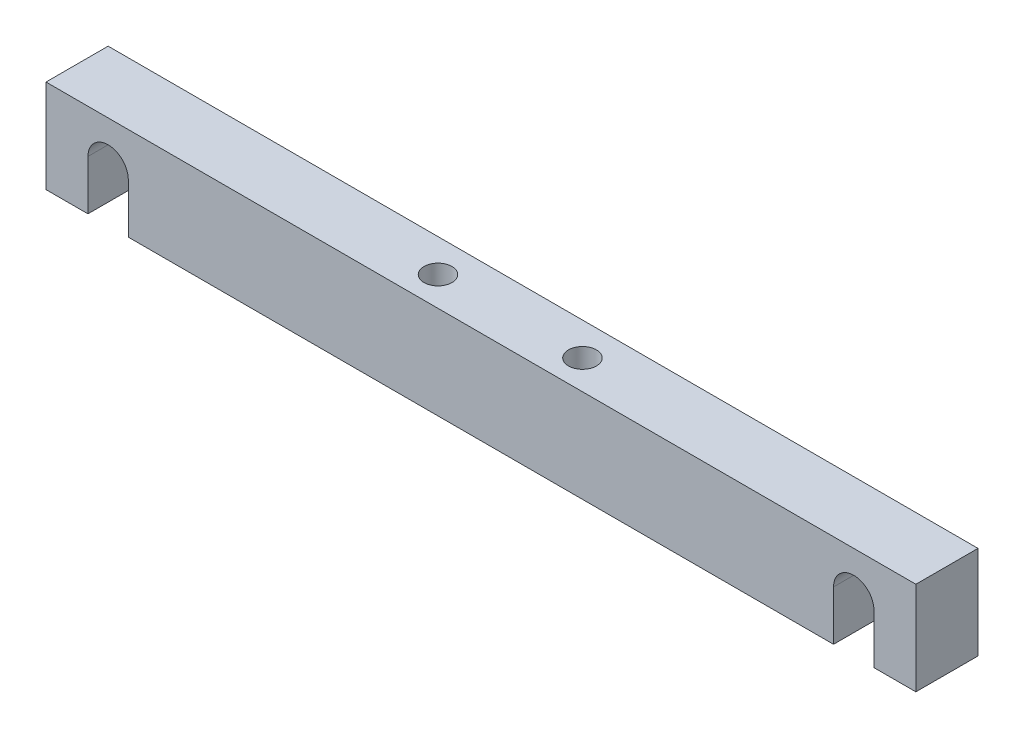
SolidWorks part; units mm, degrees
material "3.3547 (EN-AW 5083)"
ref_plane "Ebene vorne" through (0, 0, 0) normal (0, 0, 1) x (1, 0, 0)
ref_plane "Ebene oben" through (0, 0, 0) normal (0, 1, 0) x (1, 0, 0)
ref_plane "Ebene rechts" through (0, 0, 0) normal (1, 0, 0) x (0, 0, -1)
sketch "Skizze1" plane through (0, 0, 0) normal (0, 1, 0) x (1, 0, 0)
  line L1 (23.8745, 5.2866) -> (163.8745, 5.2866)
  line L2 (23.8745, 5.2866) -> (23.8745, -4.7134)
  line L3 (23.8745, -4.7134) -> (163.8745, -4.7134)
  line L4 (163.8745, 5.2866) -> (163.8745, -4.7134)
  dimension "D1" = 10
  dimension "D2" = 140
extrude "Aufsatz-Linear austragen1" add sketch "Skizze1" along normal blind 15
sketch "Skizze2" plane through (0, 0, -5.2866) normal (0, 0, -1) x (-1, 0, 0)
  line L0 (-163.8745, 15) -> (-23.8745, 15) construction
  line L1 (-37.1245, 8) -> (-37.1245, 0)
  line L2 (-163.8745, 0) -> (-23.8745, 0) construction
  line L3 (-37.1245, 0) -> (-30.6245, 0)
  line L4 (-30.6245, 0) -> (-30.6245, 8)
  line L5 (-23.8745, 15) -> (-23.8745, 0) construction
  line L6 (-157.1245, 8) -> (-157.1245, -0.1204)
  line L7 (-157.1245, -0.1204) -> (-150.6245, -0.1204)
  line L8 (-150.6245, -0.1204) -> (-150.6245, 8)
  arc A0 (-30.6245, 8) -> (-37.1245, 8) centre (-33.8745, 8) ccw
  arc A1 (-150.6245, 8) -> (-157.1245, 8) centre (-153.8745, 8) ccw
  dimension "D1" = 7
  dimension "D2" = 10
  dimension "D3" = 3.25
  dimension "D4" = 120
  dimension "D5" = 7
extrude "Schnitt-Linear austragen1" cut sketch "Skizze2" against normal blind 15
sketch "Skizze3" plane through (0, 0, 0) normal (0, -1, 0) x (1, 0, 0)
  line L0 (23.8745, -5.2866) -> (23.8745, 4.7134) construction
  circle A0 centre (82.2495, 0) radius 1.604
  circle A1 centre (105.4995, 0) radius 1.3762
  dimension "D2" = 58.375
  dimension "D1" = 81.625
hole_wizard "Formsenkung für M4 Senkschraube mit Innensechskant1" positions "3D-Skizze1" profile "Skizze4" countersink size "M4" standard "DIN" end condition through all
sketch3d "3D-Skizze1"
  point P0 (82.2495, 0, 0)
  point P3 (105.4995, 0, 0)
sketch "Skizze4" plane through (82.2495, 0, 0) normal (1, 0, 0) x (0, 0, -1)
  line L0 (0, 0) -> (0, 15)
  line L1 (0, 15) -> (2.25, 15)
  line L2 (2.25, 15) -> (2.25, 2.34)
  line L3 (2.25, 2.34) -> (4.59, 0)
  line L5 (4.59, 0) -> (0, 0)
  line L6 (-2.25, 2.34) -> (-4.59, 0) construction
  line L11 (0, -6.35) -> (0, 107.95) construction
  dimension "Bohrerdurchmesser" = 4.5
  dimension "Bohrungstiefe" = 15
  dimension "Senkdurchmesser (Oben)" = 9.18
  dimension "Senkwinkel (Oben)" = 90
